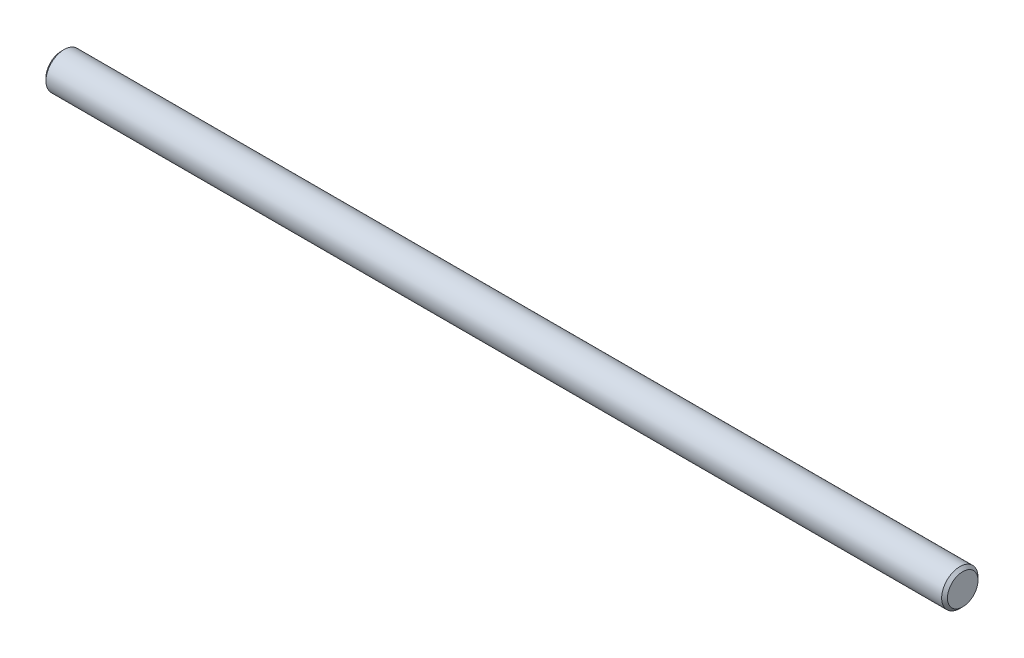
SolidWorks part; units mm, degrees
material "S235JRG2"
ref_plane "Front Plane" through (0, 0, 0) normal (0, 0, 1) x (1, 0, 0)
ref_plane "Top Plane" through (0, 0, 0) normal (0, 1, 0) x (1, 0, 0)
ref_plane "Right Plane" through (0, 0, 0) normal (1, 0, 0) x (0, 0, -1)
sketch "Sketch1" plane through (0, 0, 0) normal (1, 0, 0) x (0, 0, -1)
  circle A0 centre (0, 0) radius 12.5
  dimension "D1" = 25
extrude "Boss-Extrude1" add sketch "Sketch1" along normal mid plane 620
chamfer "Chamfer1" distance 2 angle 45 2 edges at (310, 0, -12.5) (-310, 0, -12.5)
